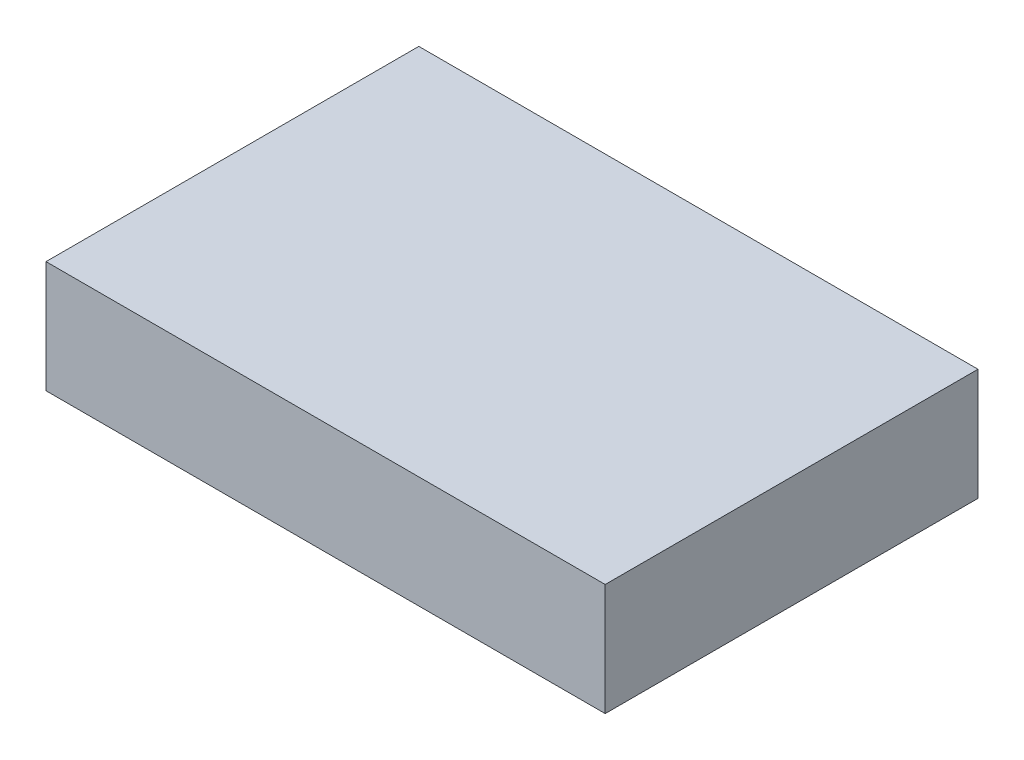
SolidWorks part; units mm, degrees
ref_plane "Front Plane" through (0, 0, 0) normal (0, 0, 1) x (1, 0, 0)
ref_plane "Top Plane" through (0, 0, 0) normal (0, 1, 0) x (1, 0, 0)
ref_plane "Right Plane" through (0, 0, 0) normal (1, 0, 0) x (0, 0, -1)
sketch "Sketch1" plane through (0, 0, 0) normal (0, 1, 0) x (1, 0, 0)
  line L1 (0, 0) -> (60, 0)
  line L2 (0, 0) -> (0, 40)
  line L3 (0, 40) -> (60, 40)
  line L4 (60, 0) -> (60, 40)
  dimension "D1" = 60
  dimension "D2" = 40
extrude "Boss-Extrude1" add sketch "Sketch1" along normal blind 12
